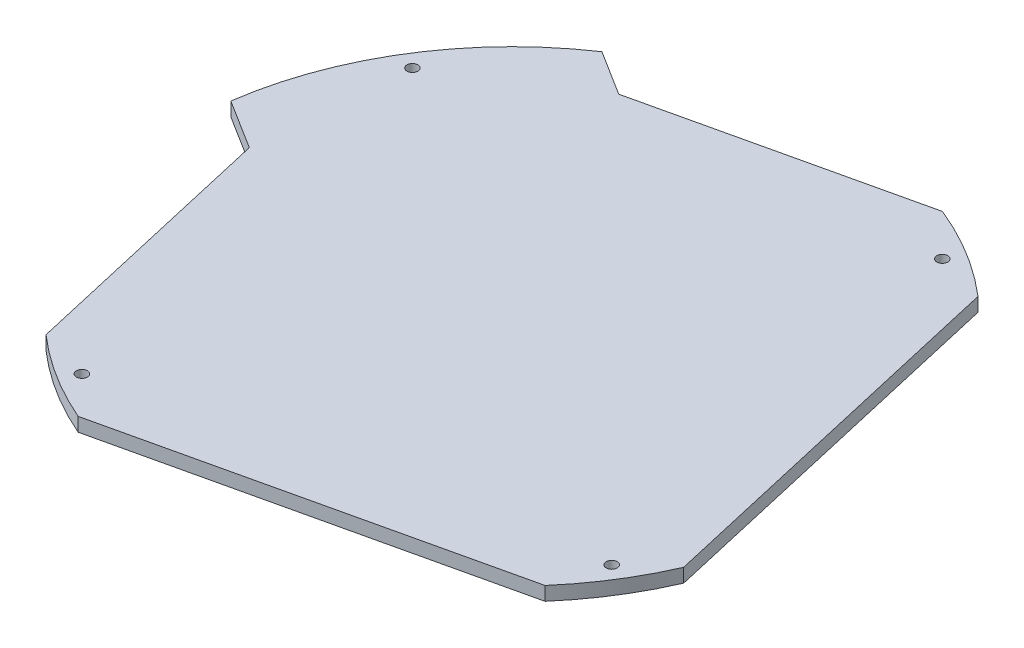
SolidWorks part; units mm, degrees
material "PE Alta densidad"
ref_plane "Alzado" through (0, 0, 0) normal (0, 0, 1) x (1, 0, 0)
ref_plane "Planta" through (0, 0, 0) normal (0, 1, 0) x (1, 0, 0)
ref_plane "Vista lateral" through (0, 0, 0) normal (1, 0, 0) x (0, 0, -1)
sketch "Croquis1" plane through (0, 0, 0) normal (0, 1, 0) x (1, 0, 0)
  line L13 (391.1172, -589.269) -> (409.1345, -600.5722)
  line L14 (409.1345, -600.5722) -> (431.0701, -696.3642)
  line L15 (462.5988, -716.1967) -> (600.5722, -684.6019)
  line L16 (620.0449, -653.6853) -> (588.2955, -515.0367)
  line L17 (555.1022, -494.7528) -> (459.4213, -516.6629)
  line L18 (459.4213, -516.6629) -> (442.9922, -506.3561)
  arc A1 (431.0701, -696.3642) -> (462.5988, -716.1967) centre (509.9541, -605.9357) ccw
  arc A2 (600.5722, -684.6019) -> (620.0449, -653.6853) centre (509.9541, -605.9357) ccw
  arc A3 (588.2955, -515.0367) -> (555.1022, -494.7528) centre (509.9541, -605.9357) ccw
  arc A4 (391.1172, -589.269) -> (442.9922, -506.3561) centre (509.9541, -605.9357) cw
extrude "Saliente-Extruir1" add sketch "Croquis1" along normal blind 5
sketch "Croquis3" plane through (0, 0, 0) normal (0, -1, 0) x (1, 0, 0)
  circle A6 centre (449.9104, 702.1695) radius 2
  circle A7 centre (413.7204, 545.892) radius 2
  circle A8 centre (569.9978, 509.702) radius 2
  circle A9 centre (606.1879, 665.9795) radius 2
extrude "Cortar-Extruir1" cut sketch "Croquis3" against normal blind 10
